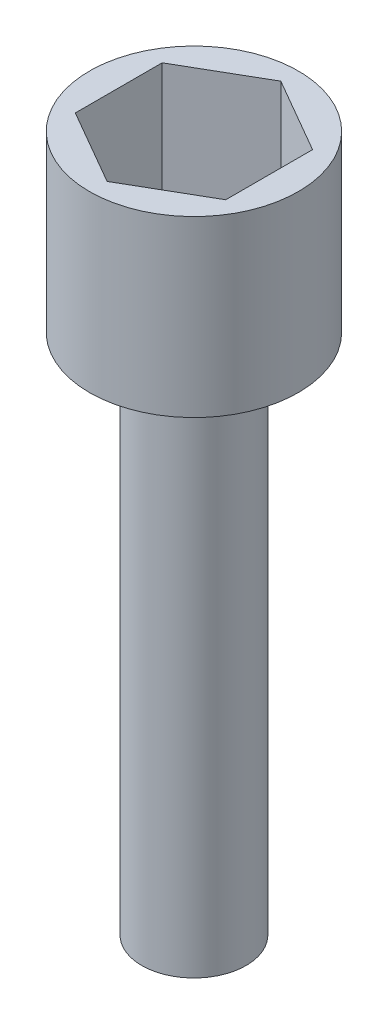
SolidWorks part; units mm, degrees
ref_plane "Plan de face" through (0, 0, 0) normal (0, 0, 1) x (1, 0, 0)
ref_plane "Plan de dessus" through (0, 0, 0) normal (0, 1, 0) x (1, 0, 0)
ref_plane "Plan de droite" through (0, 0, 0) normal (1, 0, 0) x (0, 0, -1)
sketch "Esquisse1" plane through (0, 0, 0) normal (0, 1, 0) x (1, 0, 0)
  circle A0 centre (0, 0) radius 1.5
extrude "Boss.-Extru.1" add sketch "Esquisse1" along normal blind 15
sketch "Esquisse2" plane through (0, 15, 0) normal (0, 1, 0) x (1, 0, 0)
  circle A0 centre (0, 0) radius 3
extrude "Boss.-Extru.2" add sketch "Esquisse2" along normal blind 5
sketch "Esquisse3" plane through (0, 20, 0) normal (0, 1, 0) x (1, 0, 0)
  line L1 (0, 2.4941) -> (-2.16, 1.2471)
  line L2 (-2.16, 1.2471) -> (-2.16, -1.2471)
  line L3 (-2.16, -1.2471) -> (0, -2.4941)
  line L4 (0, -2.4941) -> (2.16, -1.2471)
  line L5 (2.16, -1.2471) -> (2.16, 1.2471)
  line L6 (2.16, 1.2471) -> (0, 2.4941)
  circle A0 centre (0, 0) radius 2.16 construction
extrude "Enlèv. mat.-Extru.1" cut sketch "Esquisse3" against normal blind 4
